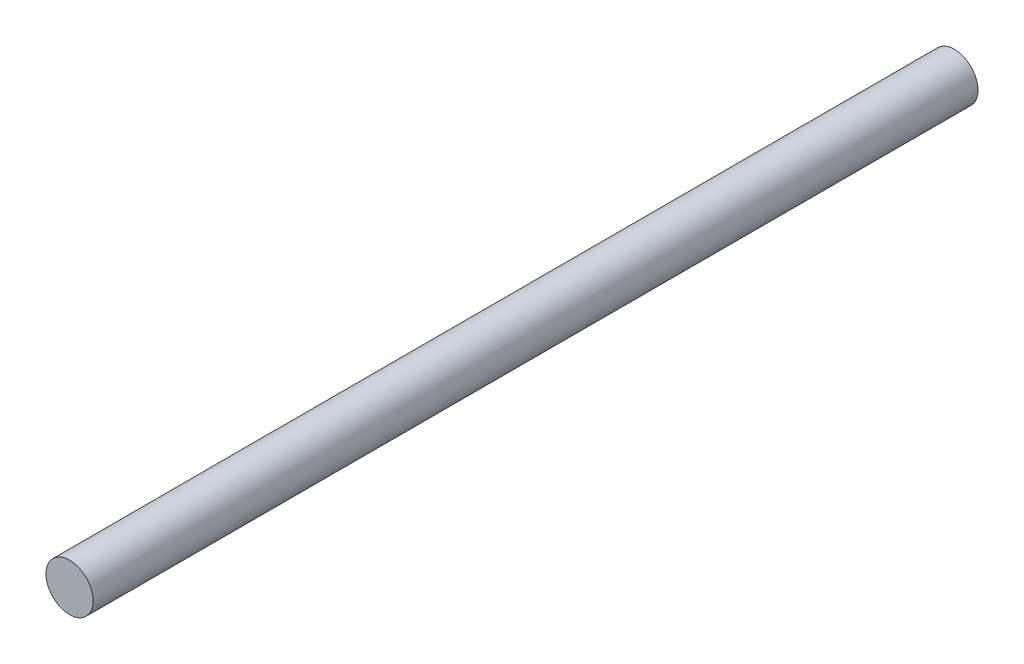
SolidWorks part; units mm, degrees
ref_plane "Front Plane" through (0, 0, 0) normal (0, 0, 1) x (1, 0, 0)
ref_plane "Top Plane" through (0, 0, 0) normal (0, 1, 0) x (1, 0, 0)
ref_plane "Right Plane" through (0, 0, 0) normal (1, 0, 0) x (0, 0, -1)
sketch "Sketch1" plane through (0, 0, 0) normal (0, 0, 1) x (1, 0, 0)
  circle A0 centre (0, 0) radius 4
  dimension "D1" = 8
extrude "Boss-Extrude1" add sketch "Sketch1" along normal blind 150
sketch "Sketch2" plane through (0, 0, 0) normal (0, 1, 0) x (1, 0, 0)
  point P0 (0, -75.1715)
